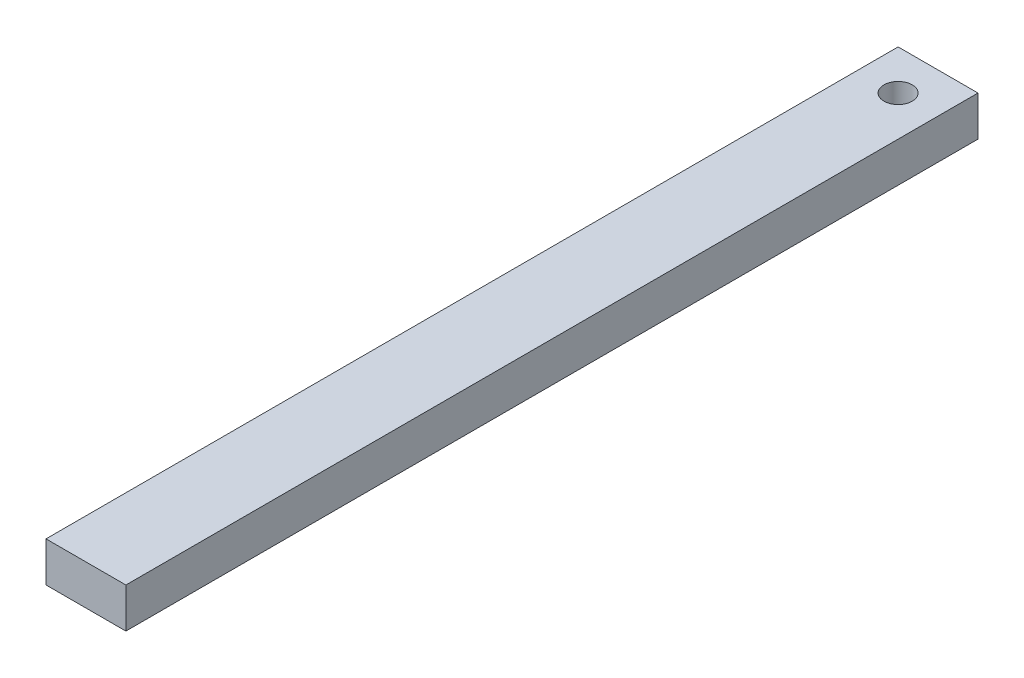
SolidWorks part; units mm, degrees
material "AISI 304"
ref_plane "Front" through (0, 0, 0) normal (0, 0, 1) x (1, 0, 0)
ref_plane "Top" through (0, 0, 0) normal (0, 1, 0) x (1, 0, 0)
ref_plane "Right" through (0, 0, 0) normal (1, 0, 0) x (0, 0, -1)
sketch "Sketch1" plane through (0, 0, 0) normal (0, 0, 1) x (1, 0, 0)
  line L1 (-9.525, -4.7625) -> (9.525, -4.7625)
  line L2 (-9.525, -4.7625) -> (-9.525, 4.7625)
  line L3 (-9.525, 4.7625) -> (9.525, 4.7625)
  line L4 (9.525, -4.7625) -> (9.525, 4.7625)
  line L5 (-9.525, -4.7625) -> (9.525, 4.7625) construction
  line L6 (-9.525, 4.7625) -> (9.525, -4.7625) construction
  point P0 (0, 0)
  dimension "D1" = 9.525
  dimension "D2" = 19.05
extrude "Boss-Extrude1" add sketch "Sketch1" along normal blind 203.2
sketch "Sketch2" plane through (0, 4.7625, 0) normal (0, 1, 0) x (1, 0, 0)
  line L0 (0, 0) -> (0, -9.525) construction
  line L1 (9.525, 0) -> (-9.525, 0) construction
  line L2 (0, -9.525) -> (0, -25.4) construction
  line L3 (-4.7625, -203.2) -> (-4.7625, -196.85) construction
  line L4 (9.525, -203.2) -> (-9.525, -203.2) construction
  line L5 (-4.7625, -196.85) -> (-9.525, -196.85) construction
  line L6 (-9.525, -203.2) -> (-9.525, 0) construction
  dimension "D1" = 15.875
  dimension "D2" = 9.525
  dimension "D3" = 6.35
  dimension "D4" = 4.7625
hole_wizard "1/4 Clearance Hole1" positions "Sketch4" profile "Sketch3" hole size "1/4" standard "ANSI Inch" end condition through all
sketch "Sketch4" plane through (0, 4.7625, 0) normal (0, 1, 0) x (1, 0, 0)
  point P3 (0, -9.525)
sketch "Sketch3" plane through (0, 4.7625, 9.525) normal (1, 0, 0) x (0, 0, 1)
  line L0 (0, 0) -> (0, 9.525)
  line L1 (0, 9.525) -> (3.3782, 9.525)
  line L2 (3.3782, 9.525) -> (3.3782, 0)
  line L5 (3.3782, 0) -> (0, 0)
  line L11 (0, -6.35) -> (0, 107.95) construction
  dimension "Thru Hole Dia." = 6.7564
  dimension "Thru Hole Depth" = 9.525
sketch "Sketch5" plane through (-9.525, 0, 0) normal (-1, 0, 0) x (0, 0, 1)
  line L0 (203.2, 4.7625) -> (0, 4.7625) construction
  line L1 (0, -4.7625) -> (69.85, -4.7625)
  line L2 (0, -4.7625) -> (0, 4.7625)
  line L3 (0, 4.7625) -> (69.85, 4.7625)
  line L4 (69.85, -4.7625) -> (69.85, 4.7625)
  dimension "D1" = 69.85
extrude "simulation" [suppressed] add sketch "Sketch5" along normal blind 2.54
mirror "Mirror1" [suppressed] about plane through (0, 0, 0) normal (1, 0, 0)
